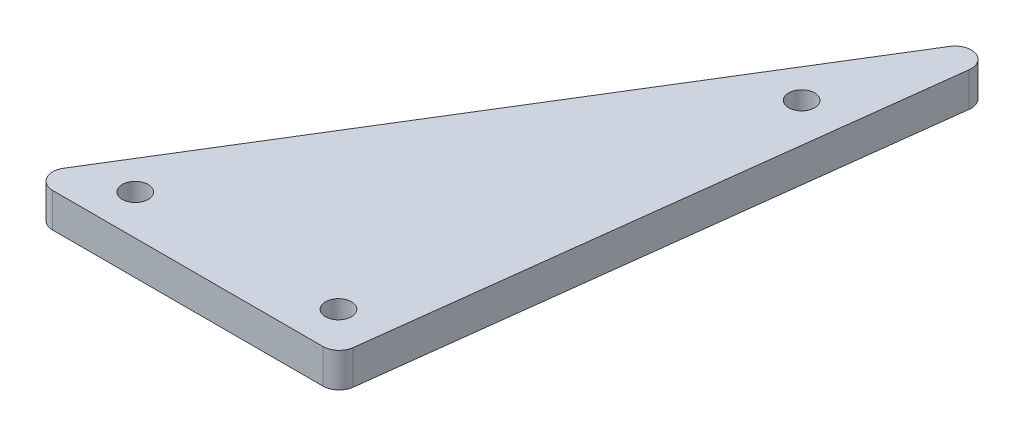
SolidWorks part; units mm, degrees
ref_plane "Front Plane" through (0, 0, 0) normal (0, 0, 1) x (1, 0, 0)
ref_plane "Top Plane" through (0, 0, 0) normal (0, 1, 0) x (1, 0, 0)
ref_plane "Right Plane" through (0, 0, 0) normal (1, 0, 0) x (0, 0, -1)
sketch "Sketch1" plane through (0, 0, 0) normal (0, 1, 0) x (1, 0, 0)
  line L0 (5.3684, 0) -> (55.3458, 0)
  line L1 (58.3235, 2.6344) -> (70.7823, 104.1037)
  line L2 (65.2496, 106.0415) -> (2.8134, 4.5722)
  arc A0 (55.3458, 0) -> (58.3235, 2.6344) centre (55.3458, 3) ccw
  arc A1 (5.3684, 0) -> (2.8134, 4.5722) centre (5.3684, 3) cw
  arc A2 (70.7823, 104.1037) -> (65.2496, 106.0415) centre (67.8047, 104.4693) ccw
  point P6 (58, 0)
  point P9 (0, 0)
  dimension "D3" = 3
  dimension "D1" = 97
  dimension "D2" = 58
  dimension "D7" = 24.605
extrude "Boss-Extrude1" add sketch "Sketch1" along normal blind 6.35
sketch "Sketch2" plane through (0, 6.35, 0) normal (0, 1, 0) x (1, 0, 0)
  line L0 (8.9457, 5) -> (52.9457, 5) construction
  line L1 (52.9457, 5) -> (63.914, 94.33) construction
  line L2 (63.914, 94.33) -> (8.9457, 5) construction
  line L6 (5.3684, 0) -> (55.3458, 0) construction
  line L7 (65.2496, 106.0415) -> (2.8134, 4.5722) construction
  circle A0 centre (13.2405, 7.4) radius 2.4
  circle A1 centre (60.1908, 83.6997) radius 2.4
  circle A2 centre (50.8224, 7.4) radius 2.4
  dimension "D6" = 4.8
  dimension "D7" = 4.8
  dimension "D8" = 4.8
  dimension "D1" = 44
  dimension "D2" = 89.33
  dimension "D3" = 97
  dimension "D4" = 5
  dimension "D5" = 5
extrude "Cut-Extrude1" cut sketch "Sketch2" against normal through all
